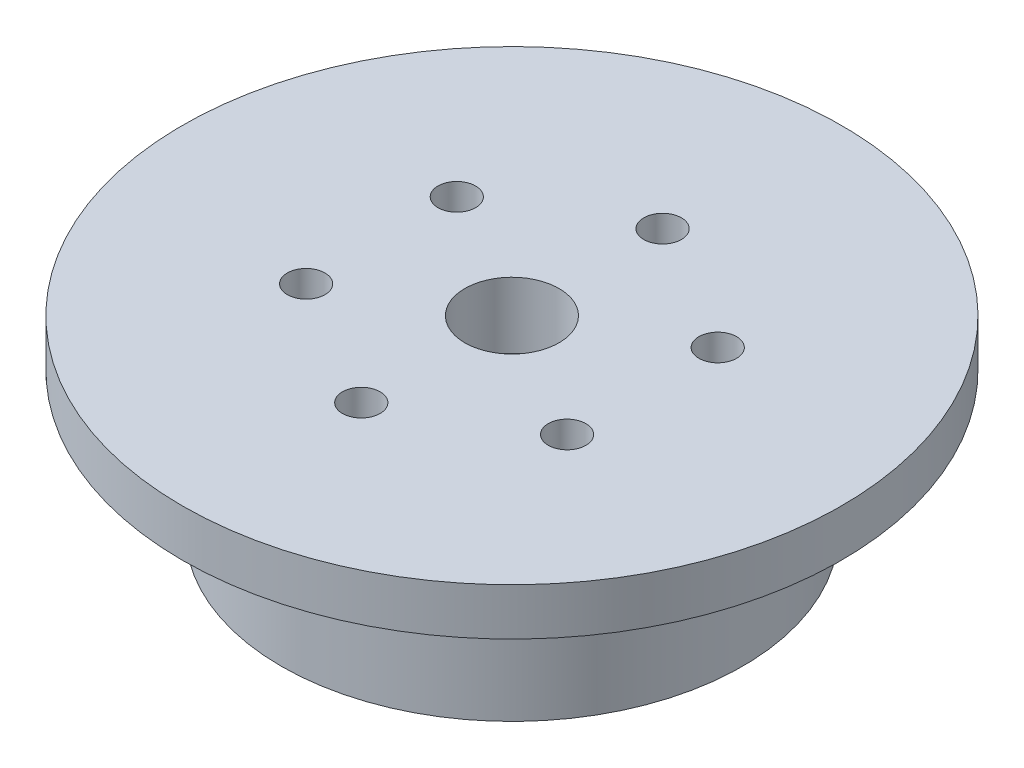
SolidWorks part; units mm, degrees
ref_plane "Alzado" through (0, 0, 0) normal (0, 0, 1) x (1, 0, 0)
ref_plane "Planta" through (0, 0, 0) normal (0, 1, 0) x (1, 0, 0)
ref_plane "Vista lateral" through (0, 0, 0) normal (1, 0, 0) x (0, 0, -1)
sketch "Croquis1" plane through (0, 0, 0) normal (0, 1, 0) x (1, 0, 0)
  circle A0 centre (0, 0) radius 35
  dimension "D1" = 70
extrude "Saliente-Extruir1" add sketch "Croquis1" along normal blind 5
sketch "Croquis2" plane through (0, 0, 0) normal (0, -1, 0) x (1, 0, 0)
  circle A0 centre (0, 0) radius 24.5
  dimension "D1" = 49
extrude "Saliente-Extruir2" add sketch "Croquis2" along normal blind 15
sketch "Croquis3" plane through (0, -15, 0) normal (0, -1, 0) x (1, 0, 0)
  circle A1 centre (0, 0) radius 6.85
  dimension "D1" = 13.7
extrude "Saliente-Extruir3" add sketch "Croquis3" along normal blind 30
sketch "Croquis4" plane through (0, 5, 0) normal (0, 1, 0) x (1, 0, 0)
  circle A0 centre (0, 0) radius 16 construction
  circle A1 centre (0, 16) radius 2
  dimension "D1" = 32
  dimension "D2" = 4
extrude "Cortar-Extruir1" cut sketch "Croquis4" against normal blind 10
pattern_circular "MatrizC1" count 6 over 360 about axis through (0, 0, 0) along (0, 1, 0) of "Cortar-Extruir1"
sketch "Croquis7" plane through (0, -45, 0) normal (0, -1, 0) x (1, 0, 0)
  line L1 (-6.3775, 2.5) -> (-3.4775, 2.5)
  line L2 (-6.3775, -2.5) -> (-3.4775, -2.5)
  line L3 (-3.4775, 2.5) -> (-3.4775, -2.5)
  circle A0 centre (0, 0) radius 6.85 construction
  circle A1 centre (0, 0) radius 6.85 construction
  arc A2 (-6.3775, 2.5) -> (-6.3775, -2.5) centre (0, 0) ccw
  point P6 (-3.4775, 0)
  dimension "D1" = 5
  dimension "D2" = 2.9
extrude "Cortar-Extruir2" cut sketch "Croquis7" against normal up to surface (30 mm away) up to face at (0, -15, -6.85)
sketch "Sketch1" plane through (0, -45, 0) normal (0, -1, 0) x (1, 0, 0)
  line L0 (-6.3775, -2.5) -> (-9.35, -2.5)
  line L1 (-9.35, 2.5) -> (-9.35, -2.5)
  line L2 (-6.3775, 2.5) -> (-9.35, 2.5)
  line L3 (-6.3775, 2.5) -> (-3.4775, 2.5)
  line L4 (-3.4775, 2.5) -> (-3.4775, -2.5)
  line L5 (-3.4775, -2.5) -> (-6.3775, -2.5)
  line L6 (-6.3775, 2.5) -> (-3.4775, 2.5) construction
  line L7 (-3.4775, 2.5) -> (-3.4775, -2.5) construction
  line L8 (-3.4775, -2.5) -> (-6.3775, -2.5) construction
  line L9 (0, 0) -> (-6.85, 0) construction
  arc A1 (-6.3775, -2.5) -> (-6.3775, 2.5) centre (0, 0) ccw
  arc A2 (-6.3775, -2.5) -> (-6.3775, 2.5) centre (0, 0) ccw
  point P4 (0, 0)
  dimension "D2" = 2.5
  dimension "D1" = 0
extrude "Cut-Extrude1" cut sketch "Sketch1" against normal offset from surface (40 mm away) 10 up to face at (12.1244, 5, -7)
sketch "Sketch2" plane through (0, 5, 0) normal (0, 1, 0) x (1, 0, 0)
  circle A0 centre (0, 0) radius 5
  dimension "D1" = 10
extrude "Cut-Extrude2" cut sketch "Sketch2" against normal blind 7
sketch "Sketch3" plane through (0, -2, 0) normal (0, 1, 0) x (1, 0, 0)
  circle A0 centre (0, 0) radius 3
  dimension "D1" = 6
extrude "Cut-Extrude3" cut sketch "Sketch3" against normal through all
